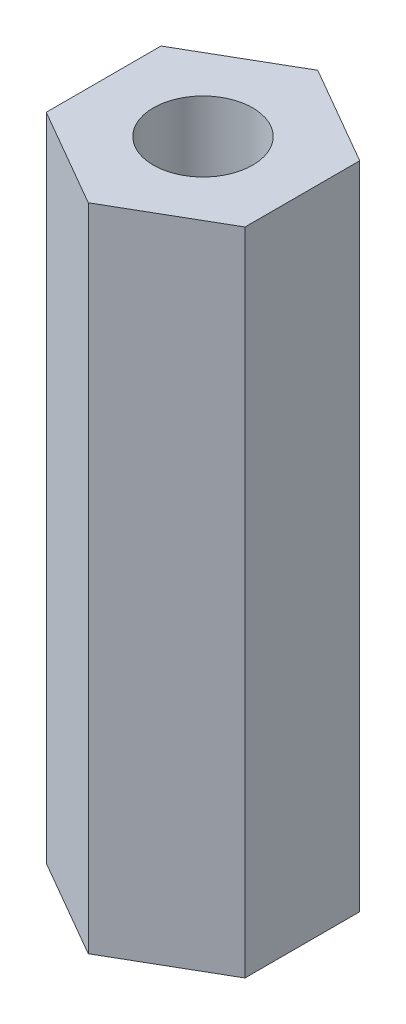
SolidWorks part; units mm, degrees
ref_plane "Front Plane" through (0, 0, 0) normal (0, 0, 1) x (1, 0, 0)
ref_plane "Top Plane" through (0, 0, 0) normal (0, 1, 0) x (1, 0, 0)
ref_plane "Right Plane" through (0, 0, 0) normal (1, 0, 0) x (0, 0, -1)
sketch "Sketch1" plane through (0, 0, 0) normal (0, 1, 0) x (1, 0, 0)
  line L1 (-2.75, 1.5877) -> (-2.75, -1.5877)
  line L2 (-2.75, -1.5877) -> (0, -3.1754)
  line L3 (0, -3.1754) -> (2.75, -1.5877)
  line L4 (2.75, -1.5877) -> (2.75, 1.5877)
  line L5 (2.75, 1.5877) -> (0, 3.1754)
  line L6 (0, 3.1754) -> (-2.75, 1.5877)
  circle A0 centre (0, 0) radius 2.75 construction
  circle A1 centre (0, 0) radius 1.375
  dimension "D2" = 2.75
  dimension "D1" = 5.5
extrude "Boss-Extrude1" add sketch "Sketch1" along normal blind 18
